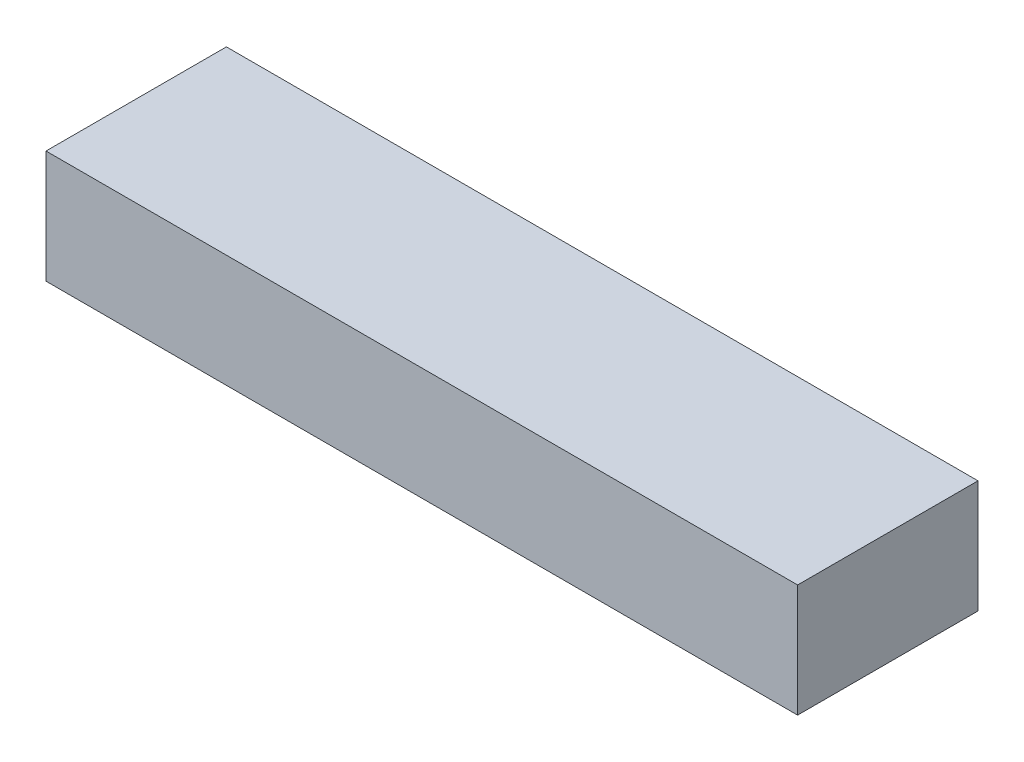
SolidWorks part; units mm, degrees
ref_plane "Front Plane" through (0, 0, 0) normal (0, 0, 1) x (1, 0, 0)
ref_plane "Top Plane" through (0, 0, 0) normal (0, 1, 0) x (1, 0, 0)
ref_plane "Right Plane" through (0, 0, 0) normal (1, 0, 0) x (0, 0, -1)
sketch "Sketch1" plane through (0, 0, 0) normal (0, 1, 0) x (1, 0, 0)
  line L1 (25, -6) -> (-25, -6)
  line L2 (25, -6) -> (25, 6)
  line L3 (25, 6) -> (-25, 6)
  line L4 (-25, -6) -> (-25, 6)
  line L5 (25, -6) -> (-25, 6) construction
  line L6 (25, 6) -> (-25, -6) construction
  point P0 (0, 0)
  dimension "D1" = 12
  dimension "D2" = 50
extrude "Boss-Extrude1" add sketch "Sketch1" along normal blind 7.5
